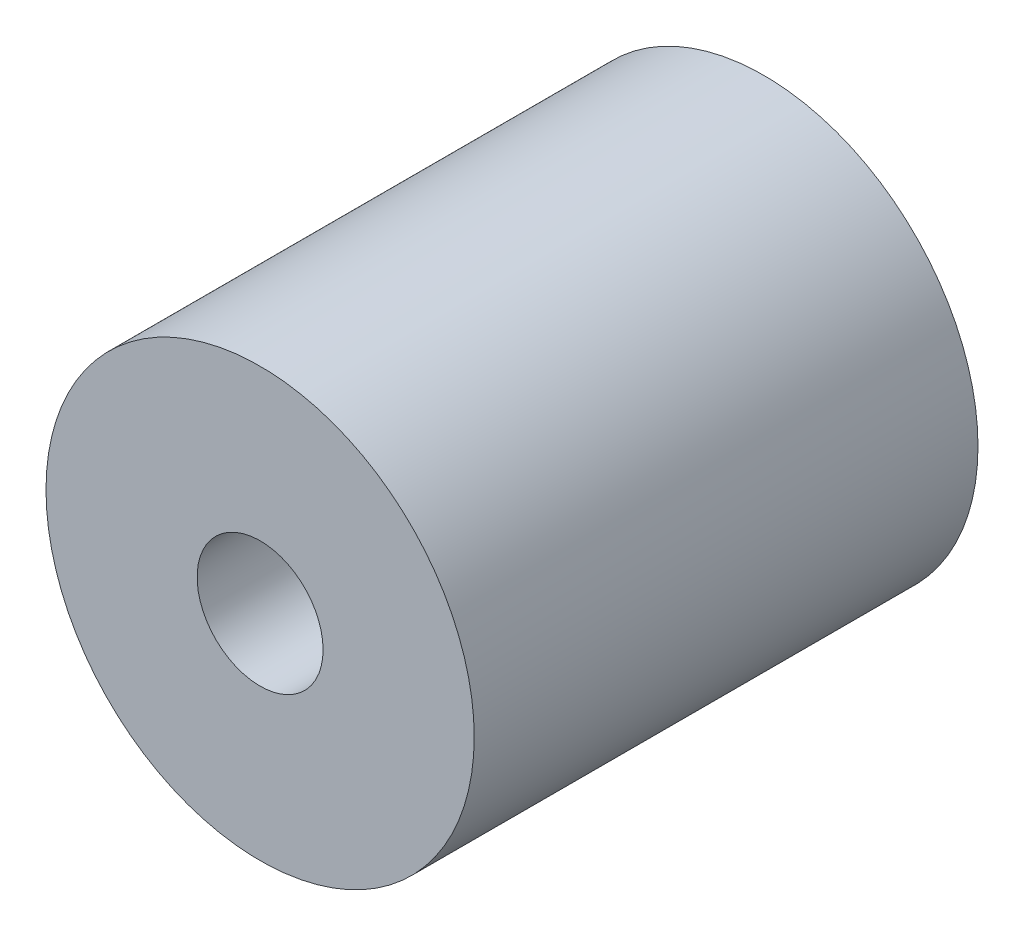
SolidWorks part; units mm, degrees
ref_plane "Front Plane" through (0, 0, 0) normal (0, 0, 1) x (1, 0, 0)
ref_plane "Top Plane" through (0, 0, 0) normal (0, 1, 0) x (1, 0, 0)
ref_plane "Right Plane" through (0, 0, 0) normal (1, 0, 0) x (0, 0, -1)
sketch "Sketch1" plane through (0, 0, 0) normal (0, 0, 1) x (1, 0, 0)
  circle A0 centre (0, 0) radius 8.5
  dimension "D1" = 17
extrude "Boss-Extrude1" add sketch "Sketch1" along normal blind 20
sketch "Sketch2" plane through (0, 0, 20) normal (0, 0, 1) x (1, 0, 0)
  circle A0 centre (0, 0) radius 2.5
  dimension "D1" = 5
extrude "Cut-Extrude1" cut sketch "Sketch2" against normal through all
